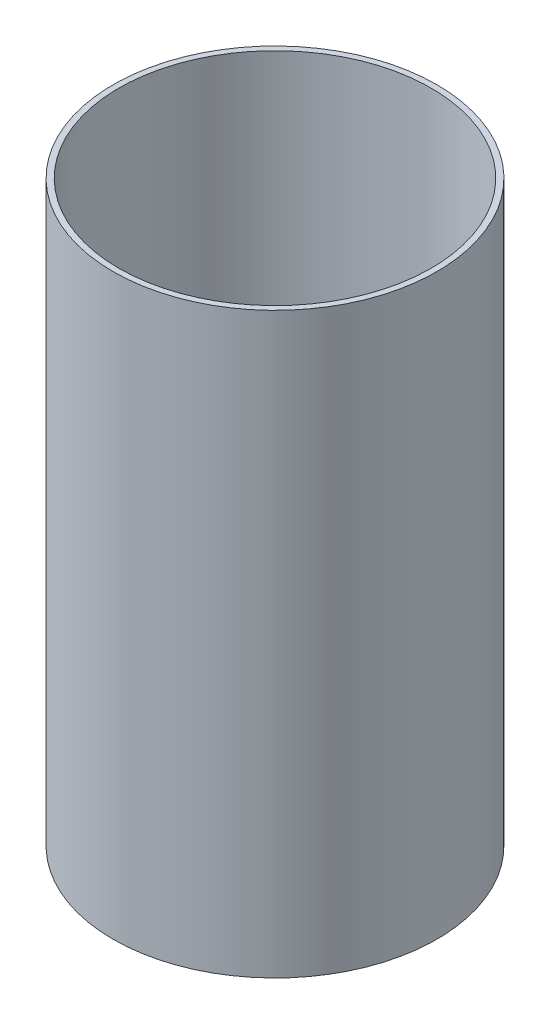
SolidWorks part; units mm, degrees
ref_plane "Front Plane" through (0, 0, 0) normal (0, 0, 1) x (1, 0, 0)
ref_plane "Top Plane" through (0, 0, 0) normal (0, 1, 0) x (1, 0, 0)
ref_plane "Right Plane" through (0, 0, 0) normal (1, 0, 0) x (0, 0, -1)
sketch "Sketch1" plane through (0, 0, 0) normal (0, 1, 0) x (1, 0, 0)
  circle A0 centre (0, 0) radius 14
  circle A1 centre (0, 0) radius 13.5
  dimension "D1" = 28
  dimension "D2" = 0.5
extrude "Boss-Extrude1" add sketch "Sketch1" along normal blind 50
